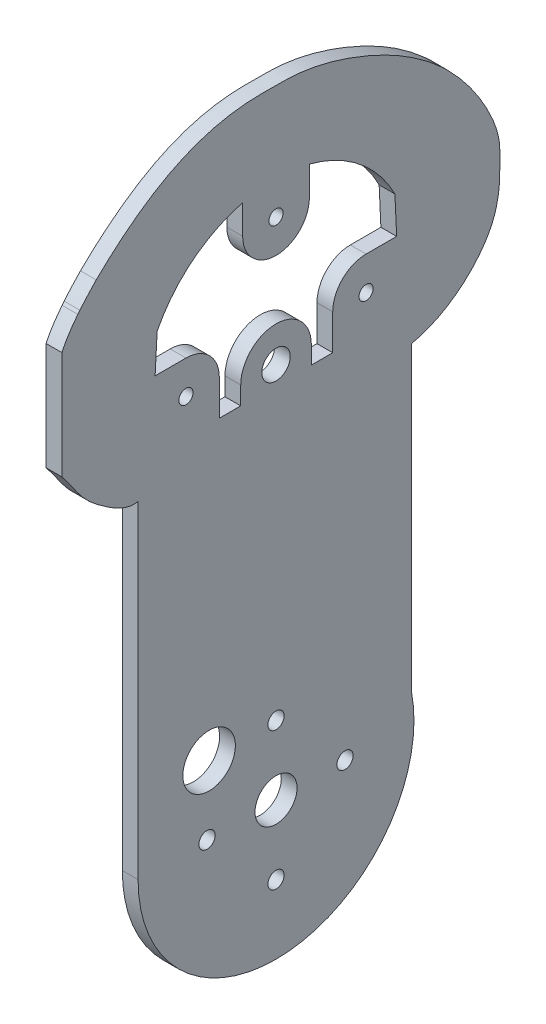
SolidWorks part; units mm, degrees
ref_plane "Plan de face" through (0, 0, 0) normal (0, 0, 1) x (1, 0, 0)
ref_plane "Plan de dessus" through (0, 0, 0) normal (0, 1, 0) x (1, 0, 0)
ref_plane "Plan de droite" through (0, 0, 0) normal (1, 0, 0) x (0, 0, -1)
sketch "Esquisse1" plane through (0, 0, 0) normal (1, 0, 0) x (0, 0, -1)
  line L19 (-6.1849, 6.1035) -> (-6.1849, 11.6469)
  line L20 (6.5151, 6.1035) -> (6.5151, 11.6469)
  line L21 (-10.6299, -14.9225) -> (-10.6299, -21.6694)
  line L22 (-16.9799, -8.5725) -> (-22.849, -8.5725)
  line L23 (17.3101, -8.5725) -> (23.1259, -8.5725)
  line L24 (-40.6082, -16.1449) -> (-40.6083, -16.3483)
  line L25 (0.1651, -90) -> (0.1651, -116.2575) construction
  line L26 (10.9601, -14.9225) -> (10.9601, -21.6694)
  line L27 (0.1651, 0) -> (0.1651, -90) construction
  line L28 (-26.0924, -27.6543) -> (-26.0924, -90) construction
  line L29 (10.9601, -21.6694) -> (6.8802, -21.6694)
  line L30 (6.8802, -21.6694) -> (6.8802, -18.2245)
  line L31 (-6.55, -18.2245) -> (-6.55, -21.6694)
  line L32 (-6.55, -21.6694) -> (-10.6299, -21.6694)
  line L33 (-26.0924, -90) -> (25.954, -90) construction
  line L34 (25.954, -90) -> (25.954, -27.6542) construction
  line L35 (-40.6082, 4.1425) -> (-40.6082, -12.7)
  line L36 (-26.0924, -27.6543) -> (-26.0924, -90)
  line L37 (25.954, -27.6542) -> (25.954, -90)
  line L38 (-40.6082, -16.1449) -> (-40.6082, -12.7)
  line L39 (-37.9035, 8.4934) -> (-36.4387, 10.3053) construction
  line L40 (-22.4631, -1.4086) -> (-22.849, -8.5725)
  line L41 (22.7933, -1.4086) -> (23.1259, -8.5725)
  circle A4 centre (-16.9799, -14.9225) radius 1.3525
  arc A5 (22.7933, -1.4086) -> (6.5151, 11.6469) centre (0.1651, -12.9465) ccw
  arc A6 (6.8802, -18.2245) -> (-6.55, -18.2245) centre (0.1651, -18.2245) ccw
  arc A7 (-37.1666, 9.4049) -> (-37.5578, 8.9143) centre (-0.9364, -19.8843) ccw
  circle A8 centre (0.1651, -18.2245) radius 2.7051
  circle A9 centre (17.3101, -14.9225) radius 1.3525
  circle A10 centre (0.1651, 6.1035) radius 1.3525
  arc A11 (-6.1849, 6.1035) -> (6.5151, 6.1035) centre (0.1651, 6.1035) ccw
  arc A12 (-6.1849, 11.6469) -> (-22.4631, -1.4086) centre (0.1651, -12.9465) ccw
  arc A13 (-10.6299, -14.9225) -> (-16.9799, -8.5725) centre (-16.9799, -14.9225) ccw
  arc A14 (-26.0924, -90) -> (25.954, -85.0614) centre (0.1651, -90) ccw
  arc A15 (17.3101, -8.5725) -> (10.9601, -14.9225) centre (17.3101, -14.9225) ccw
  circle A16 centre (0.1651, -103.1288) radius 1.55
  circle A17 centre (-12.9637, -90) radius 1.55
  circle A18 centre (0.1651, -76.8712) radius 1.55
  circle A19 centre (13.2939, -90) radius 1.55
  circle A20 centre (0.1651, -90) radius 4
  spline S5 degree 3 poles (31.4351, 15.2777) (30.2997, 16.3094) (29.1137, 17.2754) (26.6466, 19.0843) (25.3605, 19.9283) (21.4323, 22.2657) (18.7017, 23.5637) (14.4778, 25.2131) (13.0492, 25.7149) (10.8644, 26.3699) (10.1291, 26.5718) (8.6416, 26.9365) (7.8908, 27.0988) (5.638, 27.5124) (4.1274, 27.6937) (2.2253, 27.7687) (1.8441, 27.7755) (1.0809, 27.78) (0.6989, 27.7774) (-0.4463, 27.7791) (-1.2089, 27.7978) (-2.7327, 27.8153) (-3.4921, 27.8063) (-5.0041, 27.74) (-5.757, 27.6849) (-8.0062, 27.4518) (-9.4927, 27.2046) (-11.702, 26.6888) (-12.4349, 26.4915) (-13.8943, 26.0519) (-14.6221, 25.8075) (-16.7654, 25.0122) (-18.1515, 24.4005) (-20.8478, 23.0325) (-22.1587, 22.2775) (-24.7165, 20.6454) (-25.9664, 19.7652) (-28.3913, 17.9197) (-29.5674, 16.9543) (-31.2876, 15.4541) (-31.8538, 14.9457) (-32.9728, 13.9129) (-33.5258, 13.3888) (-34.0661, 12.8498) knots 0 0 0 0 0.0625 0.0625 0.125 0.125 0.25 0.25 0.3125 0.3125 0.34375 0.34375 0.375 0.375 0.4375 0.4375 0.453125 0.453125 0.46875 0.46875 0.5 0.5 0.53125 0.53125 0.5625 0.5625 0.625 0.625 0.65625 0.65625 0.6875 0.6875 0.75 0.75 0.8125 0.8125 0.875 0.875 0.9375 0.9375 0.96875 0.96875 1 1 1 1
  spline S6 degree 3 poles (-40.6083, -16.3483) (-40.3656, -16.6612) (-40.1123, -16.9655) (-39.6302, -17.5937) (-39.4007, -17.9172) (-38.719, -18.8931) (-38.2719, -19.5496) (-37.3385, -20.831) (-36.8555, -21.4585) (-36.0597, -22.3425) (-35.7819, -22.627) (-35.2029, -23.1772) (-34.9007, -23.4435) (-33.9719, -24.2127) (-33.3244, -24.6854) (-32.0108, -25.6045) (-31.3481, -26.0558) (-30.3031, -26.6606) (-29.9483, -26.8487) (-29.2225, -27.185) (-28.8514, -27.3338) (-28.0836, -27.5707) (-27.6853, -27.658) (-27.0907, -27.7154) (-26.8919, -27.7226) (-26.5928, -27.7129) (-26.493, -27.7063) (-26.293, -27.6856) (-26.1927, -27.6705) (-26.0924, -27.6543) knots 0 0 0 0 0.0625 0.0625 0.125 0.125 0.25 0.25 0.375 0.375 0.4375 0.4375 0.5 0.5 0.625 0.625 0.75 0.75 0.8125 0.8125 0.875 0.875 0.9375 0.9375 0.96875 0.96875 0.984375 0.984375 1 1 1 1
  spline S7 degree 3 poles (25.954, -27.6542) (27.1791, -27.4195) (28.3534, -27.0518) (30.0571, -26.3492) (30.6151, -26.0893) (31.7129, -25.5214) (32.2545, -25.2121) (33.8272, -24.2304) (34.814, -23.5021) (36.672, -21.9072) (37.5433, -21.0408) (38.7519, -19.6235) (39.1347, -19.135) (39.851, -18.1314) (40.1855, -17.6153) (40.8014, -16.5506) (41.0826, -16.002) (41.457, -15.1502) (41.5742, -14.8604) (41.7897, -14.2771) (41.888, -13.9835) (42.3347, -12.5068) (42.5462, -11.2963) (42.7176, -9.4515) (42.7506, -8.8307) (42.7729, -7.9005) (42.7754, -7.5904) (42.7756, -6.9702) (42.7721, -6.6601) (42.7721, -6.35) knots 0 0 0 0 0.125 0.125 0.1875 0.1875 0.25 0.25 0.375 0.375 0.5 0.5 0.5625 0.5625 0.625 0.625 0.6875 0.6875 0.71875 0.71875 0.75 0.75 0.875 0.875 0.9375 0.9375 0.96875 0.96875 1 1 1 1
  spline S8 degree 3 poles (42.7721, -6.35) (42.7721, -5.8749) (42.7838, -5.3981) (42.7897, -4.447) (42.7819, -3.973) (42.6725, -2.5632) (42.4992, -1.6375) (42.1063, -0.2679) (41.9541, 0.1856) (41.6148, 1.0877) (41.4301, 1.5303) (40.8449, 2.8393) (40.4166, 3.6895) (39.0468, 6.1905) (38.0131, 7.7873) (36.2917, 10.0821) (35.6885, 10.8307) (34.4365, 12.2817) (33.7862, 12.9857) (33.1121, 13.6686) knots 0 0 0 0 0.0625 0.0625 0.125 0.125 0.25 0.25 0.3125 0.3125 0.375 0.375 0.5 0.5 0.75 0.75 0.875 0.875 1 1 1 1
  spline S9 degree 3 poles (-37.5578, 8.9143) (-38.1429, 8.1702) (-38.7095, 7.4127) (-39.7419, 5.8248) (-40.2031, 4.9988) (-40.6082, 4.1425) knots 0 0 0 0 0.5 0.5 1 1 1 1
  spline S10 degree 3 poles (-34.0661, 12.8498) (-35.1598, 11.6922) (-36.2511, 10.5374) (-37.1666, 9.4049) knots 0 0 0 0 1 1 1 1
  spline S11 degree 2 poles (33.1121, 13.6686) (32.3322, 14.5391) (31.4351, 15.2777) knots 0 0 0 1 1 1
  point P69 (0.1651, -90)
  dimension "D2" = 4
  dimension "D3" = 8
  dimension "D4" = 3.1
  dimension "D1" = 90
sketch "Esquisse3" plane through (0, 0, 0) normal (1, 0, 0) x (0, 0, -1)
  line L0 (-6.1849, 6.1035) -> (-6.1849, 11.6469)
  line L1 (6.5151, 6.1035) -> (6.5151, 11.6469)
  line L3 (-16.9799, -8.5725) -> (-22.849, -8.5725)
  line L4 (17.3101, -8.5725) -> (23.1259, -8.5725)
  line L5 (-40.6082, -16.1449) -> (-40.6083, -16.3483)
  line L6 (0.1651, -90) -> (0.1651, -116.2575) construction
  line L7 (10.9601, -14.9225) -> (10.9601, -21.6694)
  line L8 (0.1651, 0) -> (0.1651, -90) construction
  line L9 (-26.0924, -27.6543) -> (-26.0924, -90) construction
  line L10 (10.9601, -21.6694) -> (6.8802, -21.6694)
  line L11 (6.8802, -21.6694) -> (6.8802, -18.2245)
  line L14 (-26.0924, -90) -> (25.954, -90) construction
  line L15 (25.954, -90) -> (25.954, -27.6542) construction
  line L16 (-40.6082, 4.1425) -> (-40.6082, -12.7)
  line L17 (-26.0924, -27.6543) -> (-26.0924, -90)
  line L18 (25.954, -27.6542) -> (25.954, -94.9386)
  line L19 (-40.6082, -16.1449) -> (-40.6082, -12.7)
  line L21 (-22.4631, -1.4086) -> (-22.849, -8.5725)
  line L22 (22.7933, -1.4086) -> (23.1259, -8.5725)
  line L23 (0.2749, -76.8262) -> (-12.8183, -89.9905) construction
  line L24 (-6.2717, -83.4083) -> (-18.8712, -70.8769) construction
  line L25 (0.1651, -18.2245) -> (-16.9799, -14.9225) construction
  line L26 (-12.5714, -77.1426) -> (-8.4074, -16.5735) construction
  line L27 (-10.4894, -46.8581) -> (-15.4659, -46.5159) construction
  line L28 (-17.5244, -76.4584) -> (-12.9562, -10.0101)
  line L29 (-7.5714, -77.1426) -> (-3.1182, -12.3668)
  circle A0 centre (-16.9799, -14.9225) radius 1.3525
  arc A1 (22.7933, -1.4086) -> (6.5151, 11.6469) centre (0.1651, -12.9465) ccw
  arc A2 (6.8802, -18.2245) -> (-3.1182, -12.3668) centre (0.1651, -18.2245) ccw
  arc A3 (-37.1666, 9.4049) -> (-37.5578, 8.9143) centre (-0.9364, -19.8843) ccw
  circle A4 centre (0.1651, -18.2245) radius 2.7051
  circle A5 centre (17.3101, -14.9225) radius 1.3525
  circle A6 centre (0.1651, 6.1035) radius 1.3525
  arc A7 (-6.1849, 6.1035) -> (6.5151, 6.1035) centre (0.1651, 6.1035) ccw
  arc A8 (-6.1849, 11.6469) -> (-22.4631, -1.4086) centre (0.1651, -12.9465) ccw
  arc A9 (-12.9562, -10.0101) -> (-16.9799, -8.5725) centre (-16.9799, -14.9225) ccw
  arc A10 (-26.0924, -90) -> (25.954, -94.9386) centre (0.1651, -90) ccw
  arc A11 (17.3101, -8.5725) -> (10.9601, -14.9225) centre (17.3101, -14.9225) ccw
  circle A12 centre (0.1651, -103.1288) radius 1.55
  circle A13 centre (-12.8183, -89.9905) radius 1.55
  circle A14 centre (0.2749, -76.8262) radius 1.55
  circle A15 centre (13.2939, -90) radius 1.55
  circle A16 centre (0.1651, -90) radius 4
  circle A17 centre (0.1651, -90) radius 26.2575 construction
  arc A18 (-17.5244, -76.4584) -> (-7.5714, -77.1426) centre (-12.5714, -77.1426) ccw
  spline S0 degree 3 poles (31.4351, 15.2777) (30.2997, 16.3094) (29.1137, 17.2754) (26.6466, 19.0843) (25.3605, 19.9283) (21.4323, 22.2657) (18.7017, 23.5637) (14.4778, 25.2131) (13.0492, 25.7149) (10.8644, 26.3699) (10.1291, 26.5718) (8.6416, 26.9365) (7.8908, 27.0988) (5.638, 27.5124) (4.1274, 27.6937) (2.2253, 27.7687) (1.8441, 27.7755) (1.0809, 27.78) (0.6989, 27.7774) (-0.4463, 27.7791) (-1.2089, 27.7978) (-2.7327, 27.8153) (-3.4921, 27.8063) (-5.0041, 27.74) (-5.757, 27.6849) (-8.0062, 27.4518) (-9.4927, 27.2046) (-11.702, 26.6888) (-12.4349, 26.4915) (-13.8943, 26.0519) (-14.6221, 25.8075) (-16.7654, 25.0122) (-18.1515, 24.4005) (-20.8478, 23.0325) (-22.1587, 22.2775) (-24.7165, 20.6454) (-25.9664, 19.7652) (-28.3913, 17.9197) (-29.5674, 16.9543) (-31.2876, 15.4541) (-31.8538, 14.9457) (-32.9728, 13.9129) (-33.5258, 13.3888) (-34.0661, 12.8498) knots 0 0 0 0 0.0625 0.0625 0.125 0.125 0.25 0.25 0.3125 0.3125 0.34375 0.34375 0.375 0.375 0.4375 0.4375 0.453125 0.453125 0.46875 0.46875 0.5 0.5 0.53125 0.53125 0.5625 0.5625 0.625 0.625 0.65625 0.65625 0.6875 0.6875 0.75 0.75 0.8125 0.8125 0.875 0.875 0.9375 0.9375 0.96875 0.96875 1 1 1 1
  spline S1 degree 3 poles (-40.6083, -16.3483) (-40.3656, -16.6612) (-40.1123, -16.9655) (-39.6302, -17.5937) (-39.4007, -17.9172) (-38.719, -18.8931) (-38.2719, -19.5496) (-37.3385, -20.831) (-36.8555, -21.4585) (-36.0597, -22.3425) (-35.7819, -22.627) (-35.2029, -23.1772) (-34.9007, -23.4435) (-33.9719, -24.2127) (-33.3244, -24.6854) (-32.0108, -25.6045) (-31.3481, -26.0558) (-30.3031, -26.6606) (-29.9483, -26.8487) (-29.2225, -27.185) (-28.8514, -27.3338) (-28.0836, -27.5707) (-27.6853, -27.658) (-27.0907, -27.7154) (-26.8919, -27.7226) (-26.5928, -27.7129) (-26.493, -27.7063) (-26.293, -27.6856) (-26.1927, -27.6705) (-26.0924, -27.6543) knots 0 0 0 0 0.0625 0.0625 0.125 0.125 0.25 0.25 0.375 0.375 0.4375 0.4375 0.5 0.5 0.625 0.625 0.75 0.75 0.8125 0.8125 0.875 0.875 0.9375 0.9375 0.96875 0.96875 0.984375 0.984375 1 1 1 1
  spline S2 degree 3 poles (25.954, -27.6542) (27.1791, -27.4195) (28.3534, -27.0518) (30.0571, -26.3492) (30.6151, -26.0893) (31.7129, -25.5214) (32.2545, -25.2121) (33.8272, -24.2304) (34.814, -23.5021) (36.672, -21.9072) (37.5433, -21.0408) (38.7519, -19.6235) (39.1347, -19.135) (39.851, -18.1314) (40.1855, -17.6153) (40.8014, -16.5506) (41.0826, -16.002) (41.457, -15.1502) (41.5742, -14.8604) (41.7897, -14.2771) (41.888, -13.9835) (42.3347, -12.5068) (42.5462, -11.2963) (42.7176, -9.4515) (42.7506, -8.8307) (42.7729, -7.9005) (42.7754, -7.5904) (42.7756, -6.9702) (42.7721, -6.6601) (42.7721, -6.35) knots 0 0 0 0 0.125 0.125 0.1875 0.1875 0.25 0.25 0.375 0.375 0.5 0.5 0.5625 0.5625 0.625 0.625 0.6875 0.6875 0.71875 0.71875 0.75 0.75 0.875 0.875 0.9375 0.9375 0.96875 0.96875 1 1 1 1
  spline S3 degree 3 poles (42.7721, -6.35) (42.7721, -5.8749) (42.7838, -5.3981) (42.7897, -4.447) (42.7819, -3.973) (42.6725, -2.5632) (42.4992, -1.6375) (42.1063, -0.2679) (41.9541, 0.1856) (41.6148, 1.0877) (41.4301, 1.5303) (40.8449, 2.8393) (40.4166, 3.6895) (39.0468, 6.1905) (38.0131, 7.7873) (36.2917, 10.0821) (35.6885, 10.8307) (34.4365, 12.2817) (33.7862, 12.9857) (33.1121, 13.6686) knots 0 0 0 0 0.0625 0.0625 0.125 0.125 0.25 0.25 0.3125 0.3125 0.375 0.375 0.5 0.5 0.75 0.75 0.875 0.875 1 1 1 1
  spline S4 degree 3 poles (-37.5578, 8.9143) (-38.1429, 8.1702) (-38.7095, 7.4127) (-39.7419, 5.8248) (-40.2031, 4.9988) (-40.6082, 4.1425) knots 0 0 0 0 0.5 0.5 1 1 1 1
  spline S5 degree 3 poles (-34.0661, 12.8498) (-35.1598, 11.6922) (-36.2511, 10.5374) (-37.1666, 9.4049) knots 0 0 0 0 1 1 1 1
  spline S6 degree 2 poles (33.1121, 13.6686) (32.3322, 14.5391) (31.4351, 15.2777) knots 0 0 0 1 1 1
  point P57 (0.1651, -90)
  dimension "D2" = 8
  dimension "D3" = 3.1
  dimension "D4" = 10
  dimension "D1" = 90
sketch "Esquisse4" plane through (0, 0, 0) normal (1, 0, 0) x (0, 0, -1)
  line L0 (-6.1849, 6.1035) -> (-6.1849, 11.6469)
  line L1 (6.5151, 6.1035) -> (6.5151, 11.6469)
  line L2 (-10.6299, -14.9225) -> (-10.6299, -21.6694)
  line L3 (-16.9799, -8.5725) -> (-22.849, -8.5725)
  line L4 (17.3101, -8.5725) -> (23.1259, -8.5725)
  line L5 (-40.6082, -16.1449) -> (-40.6083, -16.3483)
  line L6 (0.1651, -90) -> (0.1651, -116.2575) construction
  line L7 (10.9601, -14.9225) -> (10.9601, -21.6694)
  line L8 (0.1651, 0) -> (0.1651, -90) construction
  line L9 (-26.0924, -27.6542) -> (-26.0924, -90) construction
  line L10 (10.9601, -21.6694) -> (6.8802, -21.6694)
  line L11 (6.8802, -21.6694) -> (6.8802, -18.2245)
  line L12 (-6.55, -18.2245) -> (-6.55, -21.6694)
  line L13 (-6.55, -21.6694) -> (-10.6299, -21.6694)
  line L14 (-26.0924, -90) -> (25.954, -90) construction
  line L15 (25.954, -90) -> (25.954, -27.6542) construction
  line L16 (-40.6082, 4.1425) -> (-40.6082, -12.7)
  line L17 (-26.0924, -27.6542) -> (-26.0924, -90)
  line L18 (25.954, -27.6542) -> (25.954, -90)
  line L19 (-40.6082, -16.1449) -> (-40.6082, -12.7)
  line L21 (-22.4631, -1.4086) -> (-22.849, -8.5725)
  line L22 (22.7933, -1.4086) -> (23.1259, -8.5725)
  circle A0 centre (-16.9799, -14.9225) radius 1.3525
  arc A1 (22.7933, -1.4086) -> (6.5151, 11.6469) centre (0.1651, -12.9465) ccw
  arc A2 (6.8802, -18.2245) -> (-6.55, -18.2245) centre (0.1651, -18.2245) ccw
  arc A3 (-37.1666, 9.4049) -> (-37.5578, 8.9143) centre (-0.9364, -19.8843) ccw
  circle A4 centre (0.1651, -18.2245) radius 2.7051
  circle A5 centre (17.3101, -14.9225) radius 1.3525
  circle A6 centre (0.1651, 6.1035) radius 1.3525
  arc A7 (-6.1849, 6.1035) -> (6.5151, 6.1035) centre (0.1651, 6.1035) ccw
  arc A8 (-6.1849, 11.6469) -> (-22.4631, -1.4086) centre (0.1651, -12.9465) ccw
  arc A9 (-10.6299, -14.9225) -> (-16.9799, -8.5725) centre (-16.9799, -14.9225) ccw
  arc A10 (-26.0924, -90) -> (25.954, -85.0614) centre (0.1651, -90) ccw
  arc A11 (17.3101, -8.5725) -> (10.9601, -14.9225) centre (17.3101, -14.9225) ccw
  circle A12 centre (0.1651, -103.1288) radius 1.55
  circle A13 centre (-12.9637, -90) radius 1.55
  circle A14 centre (0.1651, -76.8712) radius 1.55
  circle A15 centre (13.2939, -90) radius 1.55
  circle A16 centre (0.1651, -90) radius 4
  circle A17 centre (-12.5714, -77.1426) radius 5
  spline S0 degree 3 poles (31.4351, 15.2777) (30.2997, 16.3094) (29.1137, 17.2754) (26.6466, 19.0843) (25.3605, 19.9283) (21.4323, 22.2657) (18.7017, 23.5637) (14.4778, 25.2131) (13.0492, 25.7149) (10.8644, 26.3699) (10.1291, 26.5718) (8.6416, 26.9365) (7.8908, 27.0988) (5.638, 27.5124) (4.1274, 27.6937) (2.2253, 27.7687) (1.8441, 27.7755) (1.0809, 27.78) (0.6989, 27.7774) (-0.4463, 27.7791) (-1.2089, 27.7978) (-2.7327, 27.8153) (-3.4921, 27.8063) (-5.0041, 27.74) (-5.757, 27.6849) (-8.0062, 27.4518) (-9.4927, 27.2046) (-11.702, 26.6888) (-12.4349, 26.4915) (-13.8943, 26.0519) (-14.6221, 25.8075) (-16.7654, 25.0122) (-18.1515, 24.4005) (-20.8478, 23.0325) (-22.1587, 22.2775) (-24.7165, 20.6454) (-25.9664, 19.7652) (-28.3913, 17.9197) (-29.5674, 16.9543) (-31.2876, 15.4541) (-31.8538, 14.9457) (-32.9728, 13.9129) (-33.5258, 13.3888) (-34.0661, 12.8498) knots 0 0 0 0 0.0625 0.0625 0.125 0.125 0.25 0.25 0.3125 0.3125 0.34375 0.34375 0.375 0.375 0.4375 0.4375 0.453125 0.453125 0.46875 0.46875 0.5 0.5 0.53125 0.53125 0.5625 0.5625 0.625 0.625 0.65625 0.65625 0.6875 0.6875 0.75 0.75 0.8125 0.8125 0.875 0.875 0.9375 0.9375 0.96875 0.96875 1 1 1 1
  spline S1 degree 3 poles (-40.6083, -16.3483) (-40.3656, -16.6612) (-40.1123, -16.9655) (-39.6302, -17.5937) (-39.4007, -17.9172) (-38.719, -18.8931) (-38.2719, -19.5496) (-37.3385, -20.831) (-36.8555, -21.4585) (-36.0597, -22.3425) (-35.7819, -22.627) (-35.2029, -23.1772) (-34.9007, -23.4435) (-33.9719, -24.2127) (-33.3244, -24.6854) (-32.0108, -25.6045) (-31.3481, -26.0558) (-30.3031, -26.6606) (-29.9483, -26.8487) (-29.2225, -27.185) (-28.8514, -27.3338) (-28.0836, -27.5707) (-27.6853, -27.658) (-27.0907, -27.7154) (-26.8919, -27.7226) (-26.5928, -27.7129) (-26.493, -27.7063) (-26.293, -27.6856) (-26.1927, -27.6705) (-26.0924, -27.6542) knots 0 0 0 0 0.0625 0.0625 0.125 0.125 0.25 0.25 0.375 0.375 0.4375 0.4375 0.5 0.5 0.625 0.625 0.75 0.75 0.8125 0.8125 0.875 0.875 0.9375 0.9375 0.96875 0.96875 0.984375 0.984375 1 1 1 1
  spline S2 degree 3 poles (25.954, -27.6542) (27.1791, -27.4195) (28.3534, -27.0518) (30.0571, -26.3492) (30.6151, -26.0893) (31.7129, -25.5214) (32.2545, -25.2121) (33.8272, -24.2304) (34.814, -23.5021) (36.672, -21.9072) (37.5433, -21.0408) (38.7519, -19.6235) (39.1347, -19.135) (39.851, -18.1314) (40.1855, -17.6153) (40.8014, -16.5506) (41.0826, -16.002) (41.457, -15.1502) (41.5742, -14.8604) (41.7897, -14.2771) (41.888, -13.9835) (42.3347, -12.5068) (42.5462, -11.2963) (42.7176, -9.4515) (42.7506, -8.8307) (42.7729, -7.9005) (42.7754, -7.5904) (42.7756, -6.9702) (42.7721, -6.6601) (42.7721, -6.35) knots 0 0 0 0 0.125 0.125 0.1875 0.1875 0.25 0.25 0.375 0.375 0.5 0.5 0.5625 0.5625 0.625 0.625 0.6875 0.6875 0.71875 0.71875 0.75 0.75 0.875 0.875 0.9375 0.9375 0.96875 0.96875 1 1 1 1
  spline S3 degree 3 poles (42.7721, -6.35) (42.7721, -5.8749) (42.7838, -5.3981) (42.7897, -4.447) (42.7819, -3.973) (42.6725, -2.5632) (42.4992, -1.6375) (42.1063, -0.2679) (41.9541, 0.1856) (41.6148, 1.0877) (41.4301, 1.5303) (40.8449, 2.8393) (40.4166, 3.6895) (39.0468, 6.1905) (38.0131, 7.7873) (36.2917, 10.0821) (35.6885, 10.8307) (34.4365, 12.2817) (33.7862, 12.9857) (33.1121, 13.6686) knots 0 0 0 0 0.0625 0.0625 0.125 0.125 0.25 0.25 0.3125 0.3125 0.375 0.375 0.5 0.5 0.75 0.75 0.875 0.875 1 1 1 1
  spline S4 degree 3 poles (-37.5578, 8.9143) (-38.1429, 8.1702) (-38.7095, 7.4127) (-39.7419, 5.8248) (-40.2031, 4.9988) (-40.6082, 4.1425) knots 0 0 0 0 0.5 0.5 1 1 1 1
  spline S5 degree 3 poles (-34.0661, 12.8498) (-35.1598, 11.6922) (-36.2511, 10.5374) (-37.1666, 9.4049) knots 0 0 0 0 1 1 1 1
  spline S6 degree 2 poles (33.1121, 13.6686) (32.3322, 14.5391) (31.4351, 15.2777) knots 0 0 0 1 1 1
  point P57 (0.1651, -90)
  dimension "D2" = 8
  dimension "D3" = 3.1
  dimension "D1" = 90
extrude "Boss.-Extru.3" add sketch "Esquisse4" along normal blind 3
